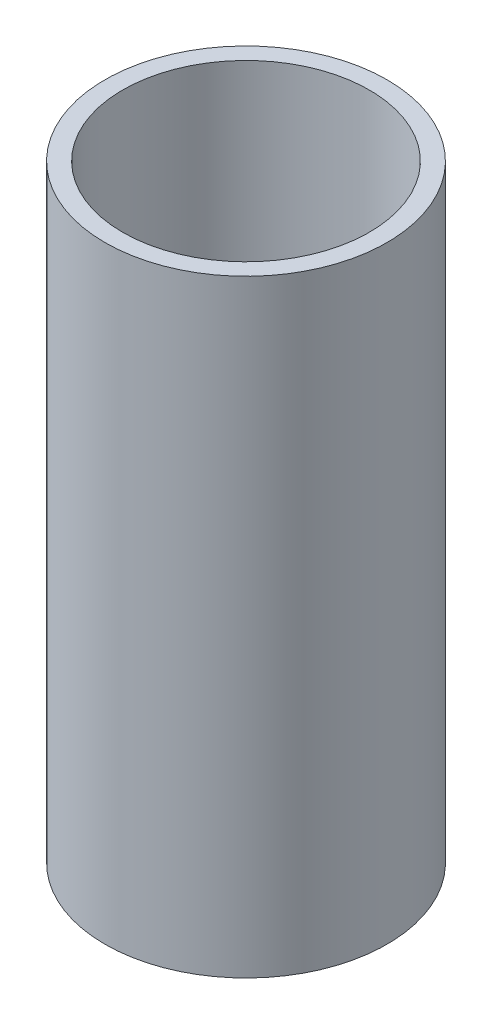
SolidWorks part; units mm, degrees
material "Polyethylene Cross-Linked"
ref_plane "Front Plane" through (0, 0, 0) normal (0, 0, 1) x (1, 0, 0)
ref_plane "Top Plane" through (0, 0, 0) normal (0, 1, 0) x (1, 0, 0)
ref_plane "Right Plane" through (0, 0, 0) normal (1, 0, 0) x (0, 0, -1)
sketch "Sketch2" plane through (0, 0, 0) normal (0, 1, 0) x (1, 0, 0)
  circle A0 centre (0, 0) radius 2.785
  dimension "D1" = 5.57
extrude "Boss-Extrude1" add sketch "Sketch2" along normal blind 12
shell "Shell1" thickness 0.35
